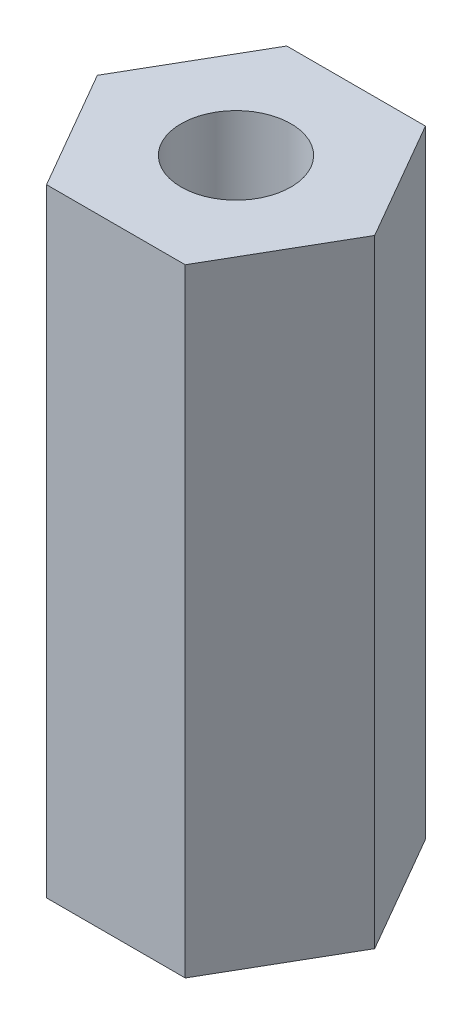
SolidWorks part; units mm, degrees
ref_plane "前视基准面" through (0, 0, 0) normal (0, 0, 1) x (1, 0, 0)
ref_plane "上视基准面" through (0, 0, 0) normal (0, 1, 0) x (1, 0, 0)
ref_plane "右视基准面" through (0, 0, 0) normal (1, 0, 0) x (0, 0, -1)
other "Configuration Table"
sketch "草图1" plane through (0, 0, 0) normal (0, 1, 0) x (1, 0, 0)
  line L1 (4.0415, 0) -> (2.0207, 3.5)
  line L2 (2.0207, 3.5) -> (-2.0207, 3.5)
  line L3 (-2.0207, 3.5) -> (-4.0415, 0)
  line L4 (-4.0415, 0) -> (-2.0207, -3.5)
  line L5 (-2.0207, -3.5) -> (2.0207, -3.5)
  line L6 (2.0207, -3.5) -> (4.0415, 0)
  circle A1 centre (0, 0) radius 1.6
  circle A2 centre (0, 0) radius 3.5 construction
  dimension "D1" = 7
  dimension "D2" = 3.2
extrude "凸台-拉伸2" add sketch "草图1" along normal blind 18
